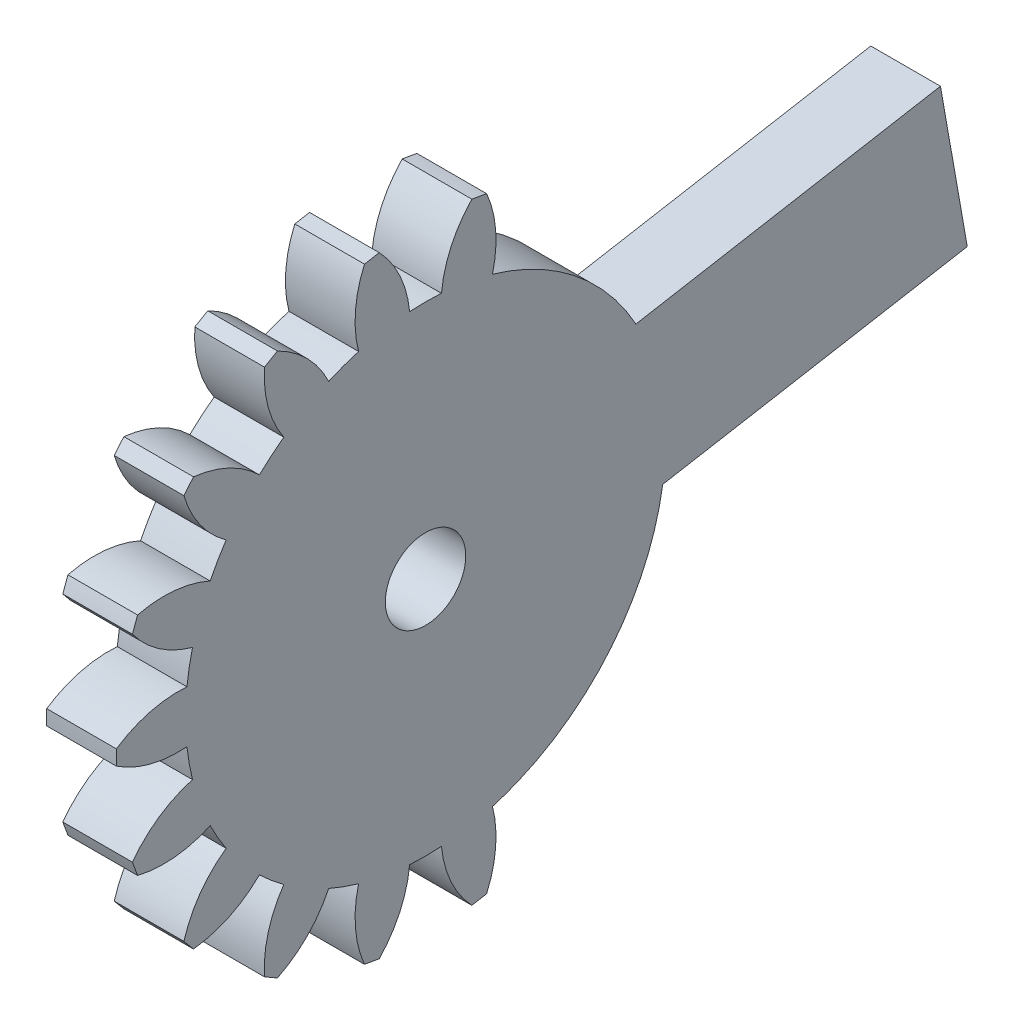
SolidWorks part; units mm, degrees
ref_plane "Plane1" through (0, 0, 0) normal (0, 0, 1) x (1, 0, 0)
ref_plane "Plane2" through (0, 0, 0) normal (0, 1, 0) x (1, 0, 0)
ref_plane "Plane3" through (0, 0, 0) normal (1, 0, 0) x (0, 0, -1)
sketch "HoldingSke" plane through (0, 0, 0) normal (0, 1, 0) x (1, 0, 0)
  line L0 (0, 0) -> (483.1367, -156.9806)
  line L1 (-15, 0) -> (100, 0) construction
  line L2 (0, 0) -> (-2.1039, 2.3779)
  line L3 (0, 0) -> (-11.863, 4.5341)
  line L4 (0, 0) -> (8.2133, 2.6687)
  line L5 (0, 0) -> (-47.5972, -17.7524)
  line L6 (0, 0) -> (-2.632, -1.7758)
  line L7 (-2.1039, 2.3779) -> (8.8308, 51.9871)
  line L8 (-76.2, 54.61) -> (-72.771, 54.61)
  line L9 (-71.009, 38.7566) -> (-53.1078, 45.2721)
  line L10 (-76.2, 71.12) -> (104.1128, 71.12)
  line L11 (0, 0) -> (-3.175, 0)
  line L12 (-76.2, 101.6) -> (-76.1492, 101.6)
  line L13 (24.9733, 27.94) -> (52.9518, 28.4284)
  line L14 (24.9733, 27.94) -> (25.0241, 27.9398)
  line L15 (24.9733, 27.94) -> (100.4021, 29.52)
  circle A0 centre (0, 0) radius 1.5875
  circle A1 centre (0, 0) radius 9.8552
  circle A2 centre (0, 0) radius 38.1
  circle A3 centre (0, 0) radius 1.5875
  dimension "MHD" = 19.7104
  dimension "Hub_dia" = 76.2
  dimension "Bore" = 3.175
  dimension "MBD" = 3.175
  dimension "Num_teeth" = 18
  dimension "Pitch_radius" = 180.3128
  dimension "Pitch" = 508
  dimension "Width" = 3.175
  dimension "Overall_len" = 50.8
  dimension "Show_teeth" = 18
  dimension "Thickness" = 3.175
  dimension "OAL" = 50.8001
  dimension "T_dim" = 3.429
  dimension "Ap" = 20
  dimension "H" = 19.05
  dimension "Backlash" = 0.0508
  dimension "Addendum_fac" = 1
  dimension "Dedendum_fac" = 1.2
  dimension "Clearance_fac" = 0.2
  dimension "Dedendum_add" = 0.0508
sketch "BasProSke" plane through (0, 0, 0) normal (0, 1, 0) x (1, 0, 0)
  line L0 (-10, 0) -> (60, 0) construction
  line L1 (0, 0) -> (0, 12.7)
  line L2 (0, 0) -> (3.175, 0)
  line L3 (3.175, 0) -> (3.175, 12.7)
  line L4 (3.175, 12.7) -> (0, 12.7)
  dimension "Diameter" = 25.4
  dimension "Thickness" = 3.175
revolve "Base-Revolve" add sketch "BasProSke" angle 360 about L0
sketch "TooCutSke" plane through (0, 0, 0) normal (1, 0, 0) x (0, 0, -1)
  line L1 (0, 0) -> (0, 107) construction
  line L2 (0, 0) -> (-1.085, 11.3784) construction
  line L3 (0, 0) -> (-3.9571, 22.4417) construction
  line L4 (-1.085, 11.3784) -> (-1.9785, 11.2208) construction
  arc A0 (0.6537, 9.8335) -> (-0.6537, 9.8335) centre (0, 0) ccw
  arc A1 (1.9234, 12.5792) -> (-1.9234, 12.5792) centre (0, 0) ccw
  circle A2 centre (0, 0) radius 11.43 construction
  circle A3 centre (0, 0) radius 10.7407 construction
  arc A4 (-0.6537, 9.8335) -> (-1.9234, 12.5792) centre (-5.2046, 9.3954) ccw
  arc A5 (1.9234, 12.5792) -> (0.6537, 9.8335) centre (5.2046, 9.3954) ccw
  dimension "Root_dia" = 19.7104
  dimension "Overcut_dia" = 25.4508
  dimension "Pitch_dia" = 22.86
  dimension "Base_dia" = 21.4814
  dimension "Flank_rad" = 4.572
  dimension "Half_ang" = 10
  dimension "Half_CT" = 0.9073
extrude "ToothCut" cut sketch "TooCutSke" along normal through all
fillet "Breaks" [suppressed] radius 0.0254
fillet "RootFillets" [suppressed] radius 0.3048
pattern_circular "TeethCuts" count 18 every 20 about axis through (-10, 0, 0) along (1, 0, 0) of "ToothCut", "RootFillets", "Breaks"
sketch "HubNeaOneSke" plane through (0, 0, 0) normal (-1, 0, 0) x (0, 0, 1)
  circle A0 centre (0, 0) radius 9.8552
  dimension "Diameter" = 19.7104
extrude "HubNearOne" [suppressed] add sketch "HubNeaOneSke" along normal blind 47.6251
sketch "HubNeaBotSke" plane through (0, 0, 0) normal (-1, 0, 0) x (0, 0, 1)
  circle A0 centre (0, 0) radius 9.8552
  dimension "Diameter" = 19.7104
extrude "HubNearBoth" [suppressed] add sketch "HubNeaBotSke" along normal blind 23.8125
ref_plane "FarPln" through (3.175, 0, 0) normal (1, 0, 0) x (0, 0, -1)
sketch "HubFarSke" plane through (3.175, 0, 0) normal (1, 0, 0) x (0, 0, -1)
  circle A0 centre (0, 0) radius 9.8552
  dimension "Diameter" = 19.7104
extrude "HubFar" [suppressed] add sketch "HubFarSke" along normal blind 23.8125
sketch "BorSke" plane through (0, 0, 0) normal (1, 0, 0) x (0, 0, -1)
  circle A0 centre (0, 0) radius 1.5875
  dimension "Diameter" = 3.175
extrude "Bore" cut sketch "BorSke" along normal mid plane 101.6001
sketch "KeySke" plane through (0, 0, 0) normal (1, 0, 0) x (0, 0, -1)
  line L0 (-0.127, 0) -> (-0.127, 1.8415)
  line L1 (-0.127, 1.8415) -> (0.127, 1.8415)
  line L2 (0.127, 1.8415) -> (0.127, 0)
  line L3 (0, 0) -> (0, 34) construction
  line L4 (-0.127, 0) -> (0.127, 0)
  dimension "Offset" = 1.8415
  dimension "Width" = 0.254
extrude "Keyway" [suppressed] cut sketch "KeySke" along normal mid plane 101.6001
pattern_circular "Keyway2" [suppressed] count 2 every 90 about axis through (-10, 0, 0) along (1, 0, 0)
sketch "Sketch3" plane through (0, 0, 0) normal (-1, 0, 0) x (0, 0, 1)
  line L0 (2.2053, 12.5071) -> (-2.2053, -12.5071) construction
  arc A0 (2.5076, 12.45) -> (1.9018, 12.5568) centre (0, 0) ccw construction
  arc A1 (-2.5076, -12.45) -> (-1.9018, -12.5568) centre (0, 0) ccw construction
sketch "Sketch7" plane through (0, 0, 0) normal (-1, 0, 0) x (0, 0, 1)
  line L0 (-8.6367, 4.7469) -> (-21.1437, 6.9522)
  line L1 (-2.8893, 9.4221) -> (-3.6524, 12.8049)
  line L3 (-3.1735, -9.3303) -> (-4.1021, -12.668)
  line L4 (-21.1437, 6.9522) -> (-22.2464, 0.6987)
  line L5 (-22.2464, 0.6987) -> (-9.7393, -1.5067)
  line L6 (2.2053, 12.5071) -> (-2.2053, -12.5071) construction
  line L8 (0.5606, -0.0988) -> (50.9626, -8.9861) construction
  circle A1 centre (0, 0) radius 9.8552 construction
  arc A2 (-3.1735, -9.3303) -> (-9.7393, -1.5067) centre (0, 0) cw
  circle A3 centre (0, 0) radius 13.3156 construction
  arc A4 (-3.6524, 12.8049) -> (-4.1021, -12.668) centre (0, 0) cw
  arc A5 (-2.8893, 9.4221) -> (-8.6367, 4.7469) centre (0, 0) ccw
  arc A6 (0.6537, 9.8335) -> (-0.6537, 9.8335) centre (0, 0) ccw construction
  circle A7 centre (0, 0) radius 1.5875 construction
  arc A8 (-2.749, 9.464) -> (-3.9775, 9.0169) centre (0, 0) ccw construction
  point P29 (-21.6951, 3.8254)
  dimension "D1" = 6.35
  dimension "D7" = 26.6313
  dimension "D2" = 12.7
  dimension "D3" = 84.453
extrude "Cut-Extrude-Thin1" cut sketch "Sketch7" against normal blind 5.08 and the other way blind 1 thin
sketch "Sketch8" plane through (0, 0, 0) normal (-1, 0, 0) x (0, 0, 1)
  line L0 (-21.1437, 6.9522) -> (-22.2464, 0.6987)
  line L1 (-21.1437, 6.9522) -> (-8.6367, 4.7469)
  line L2 (-22.2464, 0.6987) -> (-9.7393, -1.5067)
  line L3 (-8.6367, 4.7469) -> (-9.7393, -1.5067)
  arc A0 (-2.749, 9.464) -> (-8.8429, 4.3507) centre (0, 0) ccw construction
extrude "Boss-Extrude1" add sketch "Sketch8" against normal up to surface (3.175 mm away) up to face at (3.175, 0.2886, 2.9794)
sketch "Sketch9" plane through (0, 0, 0) normal (-1, 0, 0) x (0, 0, 1)
  circle A1 centre (0, 0) radius 1.651
  dimension "D1" = 3.302
extrude "Cut-Extrude2" cut sketch "Sketch9" against normal up to surface (3.175 mm away)
scale "Scale1" bodies to scale 113 scale about centroid uniform scaling no x scale factor 1 y scale factor 1.11 z scale factor 1.11
equation "' \"Pitch@HoldingSke\" = 4"
equation "' \"Num_teeth@HoldingSke\" = 12"
equation "' \"Ap@HoldingSke\" =  20"
equation "' \"Width@HoldingSke\" = 0.5"
equation "' \"Hub_dia@HoldingSke\"= 1"
equation "' \"Overall_len@HoldingSke\" = 1.0"
equation "' \"Bore@HoldingSke\" = 0.75"
equation "' \"T_dim@HoldingSke\" = 0.85"
equation "' \"Width@KeySke\" = 0.25"
equation "' \"Show_teeth@HoldingSke\" = 13"
equation "' \"Backlash@HoldingSke\" = 0.009"
equation "' \"Addendum_fac@HoldingSke\" = 1.0"
equation "' \"Dedendum_fac@HoldingSke\" = 1.25"
equation "' \"Dedendum_add@HoldingSke\" = 0.00005"
equation "' \"Clearance_fac@HoldingSke\" = 0.25"
equation "' \"Pitch@HoldingSke\" = 0.5"
equation "' \"Num_teeth@HoldingSke\" = 23"
equation "' \"Show_teeth@HoldingSke\" = 23"
equation "' \"Backlash@HoldingSke\" = 0.0375"
equation "\"Overcut_dia@TooCutSke\" = (\"Num_teeth@HoldingSke\" + 2 * \"Addendum_fac@HoldingSke\") / \"Pitch@HoldingSke\" + 0.002"
equation "\"Pitch_dia@TooCutSke\" = \"Num_teeth@HoldingSke\" / \"Pitch@HoldingSke\""
equation "\"Base_dia@TooCutSke\" = \"Num_teeth@HoldingSke\" / \"Pitch@HoldingSke\" * cos((\"Ap@HoldingSke\"  * 3.14159265 / 180))"
equation "\"Root_dia@TooCutSke\" = (\"Num_teeth@HoldingSke\" + 2) / \"Pitch@HoldingSke\" - 2 * (\"Addendum_fac@HoldingSke\" + \"Dedendum_fac@HoldingSke\") / \"Pitch@HoldingSke\" - \"Dedendum_add@HoldingSke\" * 2"
equation "\"Half_ang@TooCutSke\" = 180 / \"Num_teeth@HoldingSke\""
equation "\"Half_CT@TooCutSke\" = \"Num_teeth@HoldingSke\" / \"Pitch@HoldingSke\" * sin((3.14159265 / 2 / \"Num_teeth@HoldingSke\")) / 2 - 7 * \"Backlash@HoldingSke\" / 4"
equation "\"Flank_rad@TooCutSke\" = \"Num_teeth@HoldingSke\" / \"Pitch@HoldingSke\" / 5"
equation "\"Radius@RootFillets\" = \"Clearance_fac@HoldingSke\" / \"Pitch@HoldingSke\" + \"Dedendum_add@HoldingSke\""
equation "\"Break_rad@Breaks\" = 0.02 / \"Pitch@HoldingSke\""
equation "\"Thickness@HoldingSke\" = \"Width@HoldingSke\""
equation "\"OAL@HoldingSke\" = \"Thickness@HoldingSke\""
equation "\"MHD@HoldingSke\" = (\"Num_teeth@HoldingSke\" + 2) / \"Pitch@HoldingSke\" - 2 * (\"Addendum_fac@HoldingSke\" + \"Dedendum_fac@HoldingSke\")  / \"Pitch@HoldingSke\" - \"Dedendum_add@HoldingSke\" * 2"
equation "\"MBD@HoldingSke\" = (\"Num_teeth@HoldingSke\" + 2) / \"Pitch@HoldingSke\" - 2 * (\"Addendum_fac@HoldingSke\" + \"Dedendum_fac@HoldingSke\")  / \"Pitch@HoldingSke\" - \"Dedendum_add@HoldingSke\" * 2 - 0.002"
equation "\"MHD@HoldingSke\" = ((sgn( \"MHD@HoldingSke\" - \"Hub_dia@HoldingSke\" )-1)*( \"MHD@HoldingSke\" - \"Hub_dia@HoldingSke\" ))/-2+ \"Hub_dia@HoldingSke\""
equation "\"MBD@HoldingSke\" = ((sgn( \"MBD@HoldingSke\" - \"Bore@HoldingSke\" )-1)*( \"MBD@HoldingSke\" - \"Bore@HoldingSke\" ))/-2+ \"Bore@HoldingSke\""
equation "\"OAL@HoldingSke\" = ((sgn( \"OAL@HoldingSke\" - \"Overall_len@HoldingSke\" )+1)*( \"OAL@HoldingSke\" - \"Overall_len@HoldingSke\" ))/2 + \"Overall_len@HoldingSke\" + 0.000002"
equation "\"Num_teeth@TeethCuts\" = int( \"Show_teeth@HoldingSke\" ) + 1"
equation "\"Num_teeth@TeethCuts\" = ((sgn( \"Num_teeth@TeethCuts\" - \"Num_teeth@HoldingSke\" )-1)*( \"Num_teeth@TeethCuts\" - \"Num_teeth@HoldingSke\" ))/-2+ \"Num_teeth@HoldingSke\""
equation "\"Num_teeth@TeethCuts\" = ((sgn( \"Num_teeth@TeethCuts\" - 2.0)+1)*( \"Num_teeth@TeethCuts\" - 2.0))/2 +2.0"
equation "\"Angle@TeethCuts\" = 360.0 / \"Num_teeth@HoldingSke\""
equation "\"Diameter@BasProSke\" = (\"Num_teeth@HoldingSke\" + 2 * \"Addendum_fac@HoldingSke\") / \"Pitch@HoldingSke\""
equation "\"Thickness@BasProSke\"  = \"Thickness@HoldingSke\""
equation "' \"Fillet_rad@BasProSke\" =  \"Thickness@HoldingSke\" * 0.05"
equation "\"MHD@HoldingSke\" = ((sgn( \"MHD@HoldingSke\" - \"Root_dia@TooCutSke\" )-1)*( \"MHD@HoldingSke\" - \"Root_dia@TooCutSke\" ))/-2+ \"Root_dia@TooCutSke\""
equation "\"Diameter@HubNeaOneSke\" = \"MHD@HoldingSke\""
equation "\"Length@HubNearOne\" = \"OAL@HoldingSke\" - \"Thickness@BasProSke\""
equation "\"Diameter@HubNeaBotSke\" = \"MHD@HoldingSke\""
equation "\"Length@HubNearBoth\" = ( \"OAL@HoldingSke\" - \"Thickness@BasProSke\" ) / 2.0"
equation "\"Thickness@FarPln\" = \"Thickness@BasProSke\""
equation "\"Diameter@HubFarSke\" = \"MHD@HoldingSke\""
equation "\"Length@HubFar\" = ( \"OAL@HoldingSke\" - \"Thickness@BasProSke\" ) / 2.0"
equation "\"Diameter@BorSke\" = \"MBD@HoldingSke\""
equation "\"D1@Bore\" = \"OAL@HoldingSke\" * 2.0"
equation "\"D1@Keyway\" = \"OAL@HoldingSke\" * 2.0"
equation "\"Offset@KeySke\" = \"T_dim@HoldingSke\" - \"MBD@HoldingSke\" / 2.0"
